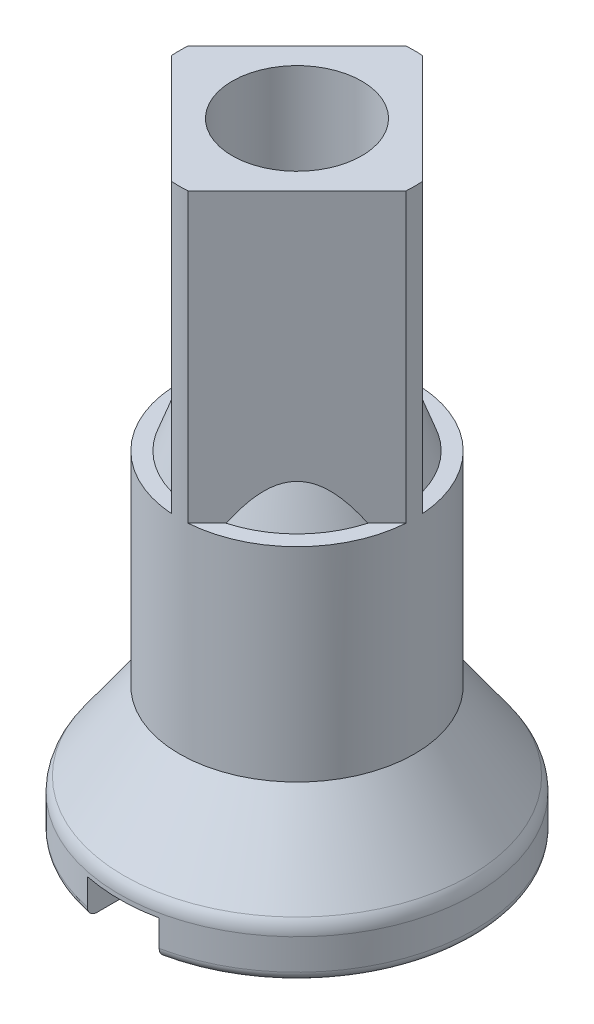
SolidWorks part; units mm, degrees
ref_plane "Front Plane" through (0, 0, 0) normal (0, 0, 1) x (1, 0, 0)
ref_plane "Top Plane" through (0, 0, 0) normal (0, 1, 0) x (1, 0, 0)
ref_plane "Right Plane" through (0, 0, 0) normal (1, 0, 0) x (0, 0, -1)
sketch "Sketch1" plane through (0, 0, 0) normal (0, 0, 1) x (1, 0, 0)
  line L0 (-7.9176, -68.62) -> (-7.9176, -81.62) construction
  line L1 (-6.5976, -81.62) -> (-4.4176, -81.62)
  line L2 (-4.2176, -81.42) -> (-4.2176, -80.7802)
  line L3 (-5.4676, -78.87) -> (-5.4676, -72.57)
  line L4 (-5.4676, -78.87) -> (-4.3107, -80.4896)
  line L5 (-5.4676, -78.87) -> (-7.9176, -78.87) construction
  line L6 (-5.4676, -68.62) -> (-5.4676, -72.57)
  line L7 (-6.5976, -68.62) -> (-5.4676, -68.62)
  line L11 (-7.9176, -75.12) -> (-6.5976, -75.12) construction
  line L12 (-6.5976, -81.62) -> (-6.5976, -68.62)
  arc A0 (-4.2176, -81.42) -> (-4.4176, -81.62) centre (-4.4176, -81.42) cw
  arc A1 (-4.2176, -80.7802) -> (-4.3107, -80.4896) centre (-4.7176, -80.7802) ccw
  point P13 (-4.2176, -81.62)
  point P16 (-4.2176, -80.62)
  dimension "D6" = 0.2
  dimension "D7" = 0.5
  dimension "D1" = 1
  dimension "D2" = 6.3
  dimension "D3" = 2.75
  dimension "D4" = 3.95
  dimension "D5" = 13
  dimension "D8" = 3.7
revolve "Revolve1" add sketch "Sketch1" angle 360 about L0
ref_plane "Plane1" through (0, -68.62, 0) normal (0, 1, 0) x (-1, 0, 0)
sketch "Sketch2" plane through (0, -68.62, 0) normal (0, 1, 0) x (-1, 0, 0)
  line L0 (5.3013, 0) -> (7.9176, -2.6163)
  line L5 (7.9176, 2.6163) -> (5.3013, 0)
  line L6 (10.5339, 0) -> (7.9176, 2.6163)
  line L7 (7.9176, -2.6163) -> (10.5339, 0)
  circle A1 centre (7.9176, 0) radius 1.85 construction
extrude "Extrude1" cut sketch "Sketch2" against normal blind 6 flip side to cut
ref_plane "Plane2" through (0, -74.62, 0) normal (0, 1, 0) x (-1, 0, 0)
sketch "Sketch3" plane through (0, -74.62, 0) normal (0, 1, 0) x (-1, 0, 0)
  circle A0 centre (7.9176, 0) radius 2.125
extrude "Extrude2" add sketch "Sketch3" along normal blind 2 draft 20
ref_plane "Plane3" through (0, -68.62, 0) normal (0, 1, 0) x (-1, 0, 0)
sketch "Sketch4" plane through (0, -68.62, 0) normal (0, 1, 0) x (-1, 0, 0)
  circle A0 centre (7.9176, 0) radius 1.35
extrude "Extrude3" cut sketch "Sketch4" against normal blind 12
ref_plane "Plane4" through (0, -81.62, 0) normal (0, -1, 0) x (1, 0, 0)
sketch "Sketch5" plane through (0, -81.62, 0) normal (0, -1, 0) x (1, 0, 0)
  line L0 (-7.9176, 3.7) -> (-7.9176, -3.7) construction
  line L2 (-8.6676, 0) -> (-7.1676, 0) construction
  line L3 (-8.6676, 3.75) -> (-8.6676, -3.75)
  line L4 (-8.6676, -3.75) -> (-7.1676, -3.75)
  line L9 (-7.1676, 3.75) -> (-7.1676, -3.75)
  line L10 (-8.6676, 3.75) -> (-7.1676, 3.75)
  circle A0 centre (-7.9176, 0) radius 3.7 construction
extrude "Extrude4" cut sketch "Sketch5" against normal blind 0.75
